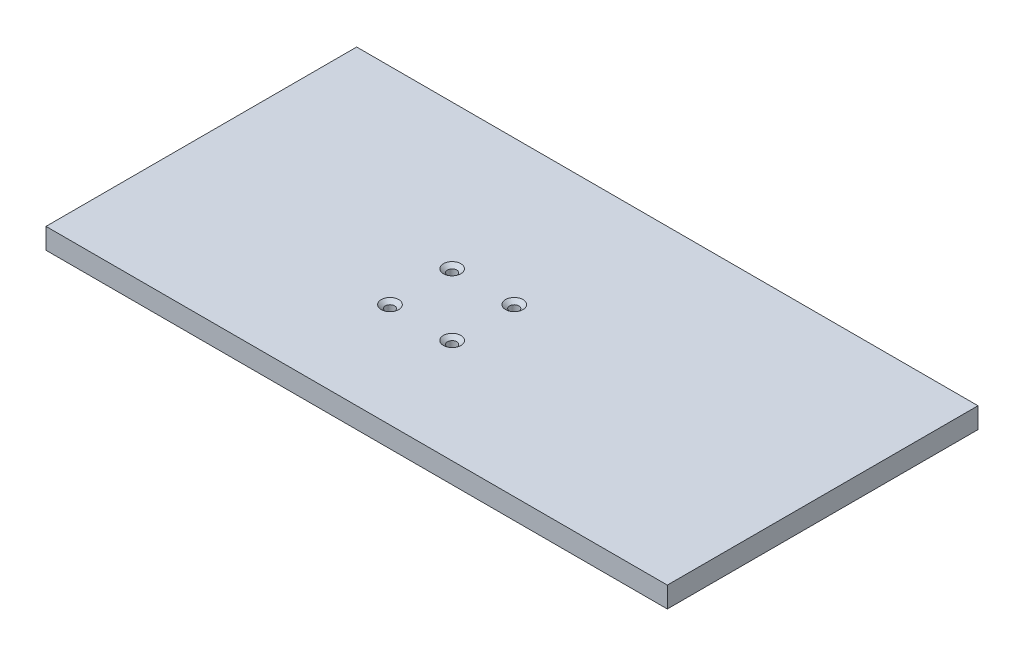
SolidWorks part; units mm, degrees
ref_plane "Front Plane" through (0, 0, 0) normal (0, 0, 1) x (1, 0, 0)
ref_plane "Top Plane" through (0, 0, 0) normal (0, 1, 0) x (1, 0, 0)
ref_plane "Right Plane" through (0, 0, 0) normal (1, 0, 0) x (0, 0, -1)
sketch "Sketch1" plane through (0, 0, 0) normal (0, 1, 0) x (1, 0, 0)
  line L1 (150, -75) -> (-150, -75)
  line L2 (150, -75) -> (150, 75)
  line L3 (150, 75) -> (-150, 75)
  line L4 (-150, -75) -> (-150, 75)
  line L5 (150, -75) -> (-150, 75) construction
  line L6 (150, 75) -> (-150, -75) construction
  point P0 (0, 0)
  dimension "D1" = 300
  dimension "D2" = 150
extrude "Boss-Extrude1" add sketch "Sketch1" along normal blind 10
hole_wizard "CSK for #8 Flat Head Machine Screw (100)1" positions "Sketch2" profile "Sketch4" countersink size "#8" standard "ANSI Inch" end condition up to next
sketch "Sketch2" plane through (0, 10, 0) normal (0, 1, 0) x (1, 0, 0)
  point P4 (-4.2442, 5.3351)
  point P7 (-4.2442, -24.6649)
  point P10 (-34.2442, -24.6649)
  point P15 (-34.2442, 5.3351)
sketch "Sketch4" plane through (-4.2442, 10, -5.3351) normal (1, 0, 0) x (0, 0, 1)
  line L0 (0, 0) -> (0, 10)
  line L1 (0, 10) -> (2.2479, 10)
  line L2 (2.2479, 10) -> (2.2479, 1.6518)
  line L3 (2.2479, 1.6518) -> (4.2164, 0)
  line L5 (4.2164, 0) -> (0, 0)
  line L6 (-2.2479, 1.6518) -> (-4.2164, 0) construction
  line L11 (0, -6.35) -> (0, 107.95) construction
  dimension "Thru Hole Dia." = 4.4958
  dimension "Thru Hole Depth" = 10
  dimension "Near C'Sink Dia." = 8.4328
  dimension "Near C'Sink Angle" = 100
